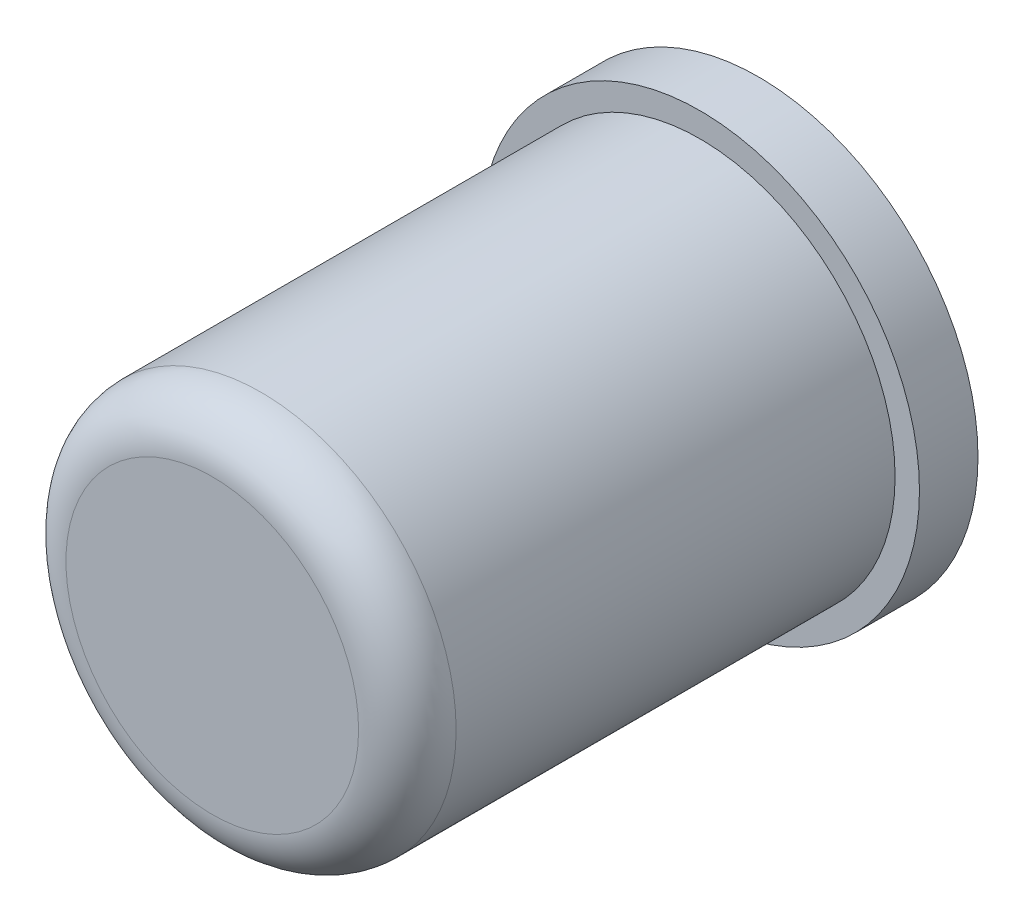
SolidWorks part; units mm, degrees
ref_plane "前视基准面" through (0, 0, 0) normal (0, 0, 1) x (1, 0, 0)
ref_plane "上视基准面" through (0, 0, 0) normal (0, 1, 0) x (1, 0, 0)
ref_plane "右视基准面" through (0, 0, 0) normal (1, 0, 0) x (0, 0, -1)
sketch "草图1" plane through (0, 0, 0) normal (0, 0, 1) x (1, 0, 0)
  circle A0 centre (0, 0) radius 4.5
extrude "凸台-拉伸1" add sketch "草图1" along normal blind 1.2
sketch "草图2" plane through (0, 0, 1.2) normal (0, 0, 1) x (1, 0, 0)
  circle A0 centre (0, 0) radius 4
extrude "凸台-拉伸2" add sketch "草图2" along normal blind 10
fillet "圆角1" radius 1 1 edges at (4, 0, 11.2)
